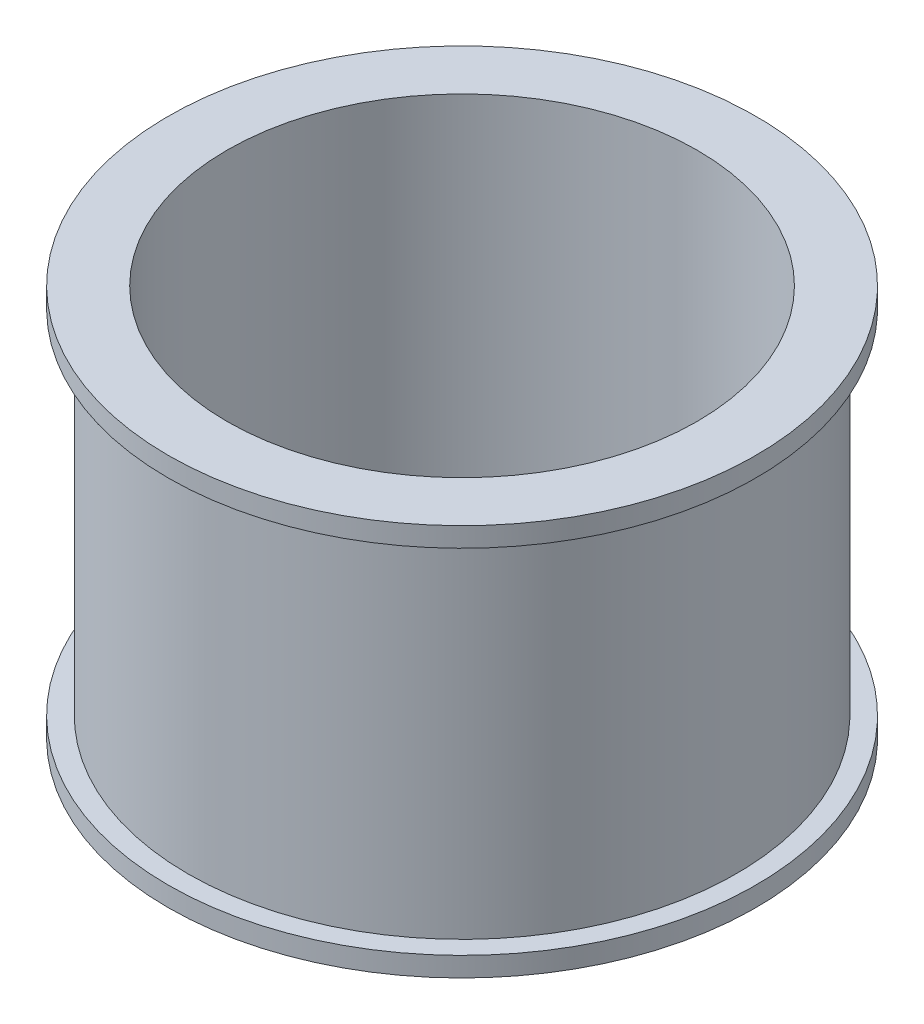
SolidWorks part; units mm, degrees
ref_plane "Front Plane" through (0, 0, 0) normal (0, 0, 1) x (1, 0, 0)
ref_plane "Top Plane" through (0, 0, 0) normal (0, 1, 0) x (1, 0, 0)
ref_plane "Right Plane" through (0, 0, 0) normal (1, 0, 0) x (0, 0, -1)
sketch "Sketch1" plane through (0, 0, 0) normal (0, 1, 0) x (1, 0, 0)
  circle A0 centre (0, 0) radius 3.5
  dimension "D1" = 7
extrude "Boss-Extrude1" add sketch "Sketch1" along normal blind 5
sketch "Sketch2" plane through (0, 5, 0) normal (0, 1, 0) x (1, 0, 0)
  circle A0 centre (0, 0) radius 3
  dimension "D1" = 6
extrude "Cut-Extrude1" cut sketch "Sketch2" against normal blind 10 contours A0
sketch "Sketch16" plane through (0, 5, 0) normal (0, 1, 0) x (1, 0, 0)
  circle A0 centre (0, 0) radius 3.5
  circle A1 centre (0, 0) radius 3.75
  dimension "D1" = 7
  dimension "D2" = 7.5
extrude "Boss-Extrude2" add sketch "Sketch16" against normal blind 0.25
ref_plane "Plane1" through (0, 2.5, 0) normal (0, 1, 0) x (1, 0, 0)
mirror "Mirror1" about plane through (0, 2.5, 0) normal (0, 1, 0) of "Boss-Extrude2"
